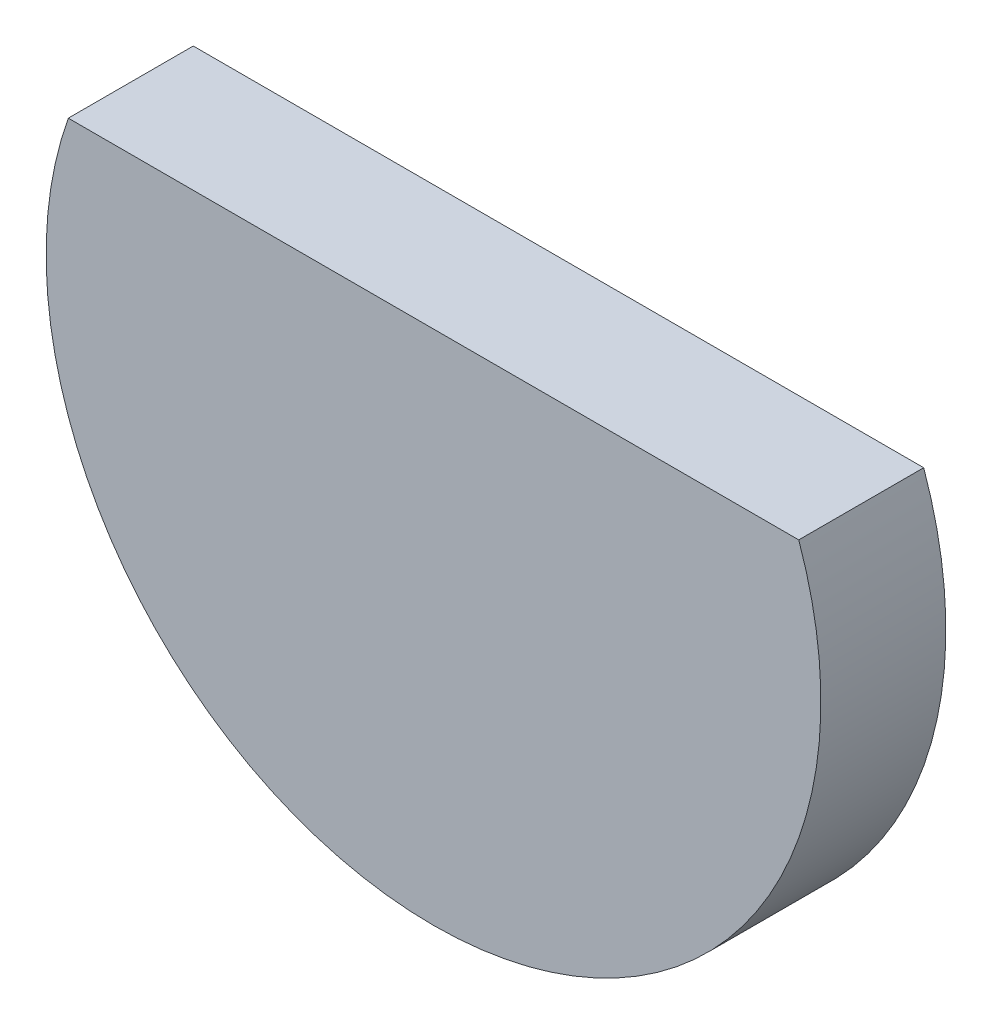
SolidWorks part; units mm, degrees
ref_plane "Front Plane" through (0, 0, 0) normal (0, 0, 1) x (1, 0, 0)
ref_plane "Top Plane" through (0, 0, 0) normal (0, 1, 0) x (1, 0, 0)
ref_plane "Right Plane" through (0, 0, 0) normal (1, 0, 0) x (0, 0, -1)
sketch "Sketch1" plane through (0, 0, 0) normal (0, 0, 1) x (1, 0, 0)
  circle A0 centre (0, 0) radius 12.4
  dimension "D1" = 24.8
extrude "Boss-Extrude1" add sketch "Sketch1" along normal blind 4
sketch "Sketch2" plane through (0, 0, 4) normal (0, 0, 1) x (1, 0, 0)
  line L0 (0, -12.4) -> (0, 4.1333) construction
  line L1 (-11.6908, 4.1333) -> (11.6908, 4.1333)
  circle A0 centre (0, 0) radius 12.4 construction
  circle A2 centre (0, 0) radius 12.4
  arc A3 (11.6908, 4.1333) -> (-11.6908, 4.1333) centre (0, 0) ccw
  point P8 (0, 4.1333)
  dimension "D2" = 16.5333
  dimension "D1" = 0
extrude "Cut-Extrude1" cut sketch "Sketch2" against normal blind 4
